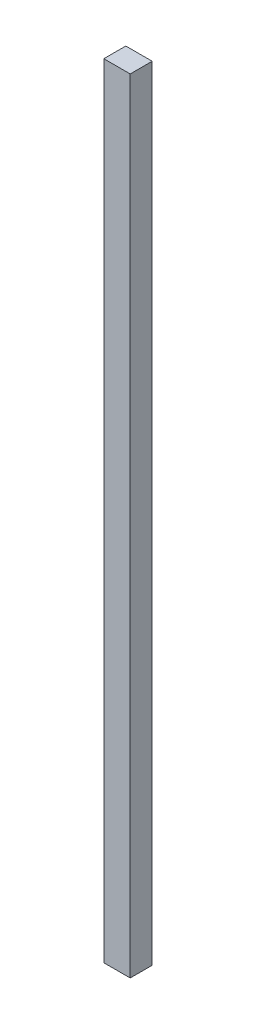
SolidWorks part; units mm, degrees
ref_plane "前视基准面" through (0, 0, 0) normal (0, 0, 1) x (1, 0, 0)
ref_plane "上视基准面" through (0, 0, 0) normal (0, 1, 0) x (1, 0, 0)
ref_plane "右视基准面" through (0, 0, 0) normal (1, 0, 0) x (0, 0, -1)
other "Configuration Table"
sketch "草图1" plane through (0, 0, 0) normal (0, 0, 1) x (1, 0, 0)
  line L0 (0, 0) -> (6, 0)
  line L1 (6, 0) -> (6, 178)
  line L2 (6, 178) -> (0, 178)
  line L3 (0, 178) -> (0, 0)
  dimension "width" = 6
  dimension "height" = 178
extrude "Fixed_upright" add sketch "草图1" along normal blind 5
